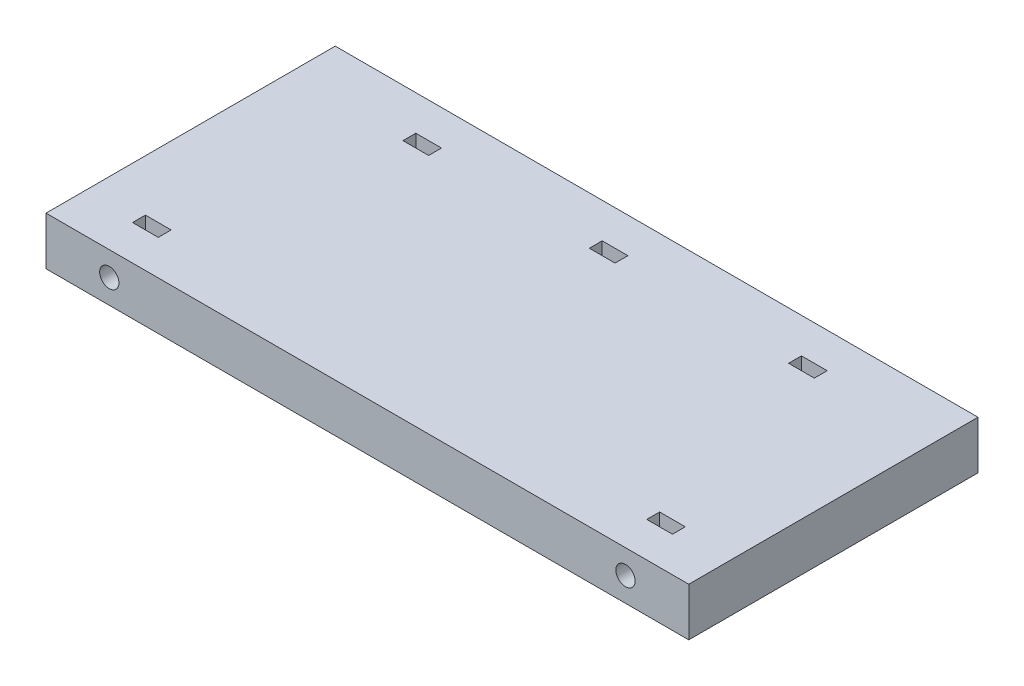
SolidWorks part; units mm, degrees
ref_plane "Front Plane" through (0, 0, 0) normal (0, 0, 1) x (1, 0, 0)
ref_plane "Top Plane" through (0, 0, 0) normal (0, 1, 0) x (1, 0, 0)
ref_plane "Right Plane" through (0, 0, 0) normal (1, 0, 0) x (0, 0, -1)
sketch "Sketch1" plane through (0, 0, 0) normal (0, 1, 0) x (1, 0, 0)
  line L1 (-105.1314, 56.7929) -> (94.8686, 56.7929)
  line L2 (-105.1314, 56.7929) -> (-105.1314, -33.2071)
  line L3 (-105.1314, -33.2071) -> (94.8686, -33.2071)
  line L4 (94.8686, 56.7929) -> (94.8686, -33.2071)
  line L5 (50.8686, 45.8608) -> (50.8686, 41.8608)
  line L6 (-97.6314, 52.8254) -> (-97.6314, 56.7929) construction
  line L7 (-97.6314, 56.7929) -> (-97.6314, -36.8782) construction
  line L8 (58.8686, 41.8608) -> (50.8686, 41.8608)
  line L9 (-69.1314, 45.8608) -> (-61.1314, 45.8608)
  line L10 (-69.1314, 45.8608) -> (-69.1314, 41.8608)
  line L11 (-69.1314, 41.8608) -> (-61.1314, 41.8608)
  line L12 (-61.1314, 45.8608) -> (-61.1314, 41.8608)
  line L13 (58.8686, 45.8608) -> (58.8686, 41.8608)
  line L14 (58.8686, 45.8608) -> (50.8686, 45.8608)
  line L16 (-11.1314, 45.8608) -> (-3.1314, 45.8608)
  line L17 (-11.1314, 45.8608) -> (-11.1314, 41.8608)
  line L18 (-11.1314, 41.8608) -> (-3.1314, 41.8608)
  line L19 (-3.1314, 45.8608) -> (-3.1314, 41.8608)
  line L26 (70.8686, -22.2751) -> (70.8686, -18.2751)
  line L27 (78.8686, -22.2751) -> (70.8686, -22.2751)
  line L28 (78.8686, -22.2751) -> (78.8686, -18.2751)
  line L29 (78.8686, -18.2751) -> (70.8686, -18.2751)
  line L30 (-81.1314, -22.2751) -> (-81.1314, -18.2751)
  line L31 (-89.1314, -22.2751) -> (-89.1314, -18.2751)
  line L32 (-89.1314, -18.2751) -> (-81.1314, -18.2751)
  line L33 (-89.1314, -22.2751) -> (-81.1314, -22.2751)
  dimension "D3" = 8
  dimension "D1" = 200
  dimension "D2" = 90
  dimension "D5" = 94
  dimension "D6" = 7.5
  dimension "D7" = 8
  dimension "D8" = 4
  dimension "D9" = 36
extrude "Boss-Extrude1" add sketch "Sketch1" along normal blind 15
sketch "Sketch2" plane through (0, 0, -56.7929) normal (0, 0, -1) x (-1, 0, 0)
  line L0 (-94.8686, 7.5) -> (143.5237, 7.5) construction
  line L1 (-94.8686, 15) -> (-94.8686, 0) construction
  line L2 (5.1314, 15) -> (5.1314, -7.5506) construction
  line L3 (-94.8686, 15) -> (105.1314, 15) construction
  circle A0 centre (-54.8686, 7.5) radius 3
  circle A1 centre (5.1314, 7.5) radius 3
  circle A3 centre (65.1314, 7.5) radius 3
  dimension "D1" = 6
  dimension "D3" = 6
  dimension "D2" = 40
extrude "Cut-Extrude1" cut sketch "Sketch2" against normal blind 20
sketch "Sketch3" plane through (0, 0, 33.2071) normal (0, 0, 1) x (1, 0, 0)
  line L0 (-105.1314, 7.5) -> (94.8686, 7.5) construction
  line L1 (-105.1314, 15) -> (-105.1314, 0) construction
  line L2 (94.8686, 15) -> (94.8686, 0) construction
  line L3 (-5.1314, 15) -> (-5.1314, -3.8529) construction
  line L4 (-105.1314, 15) -> (94.8686, 15) construction
  circle A0 centre (-85.445, 7.5) radius 3
  circle A1 centre (75.1822, 7.5) radius 3
  dimension "D1" = 6
extrude "Cut-Extrude2" cut sketch "Sketch3" against normal blind 20
